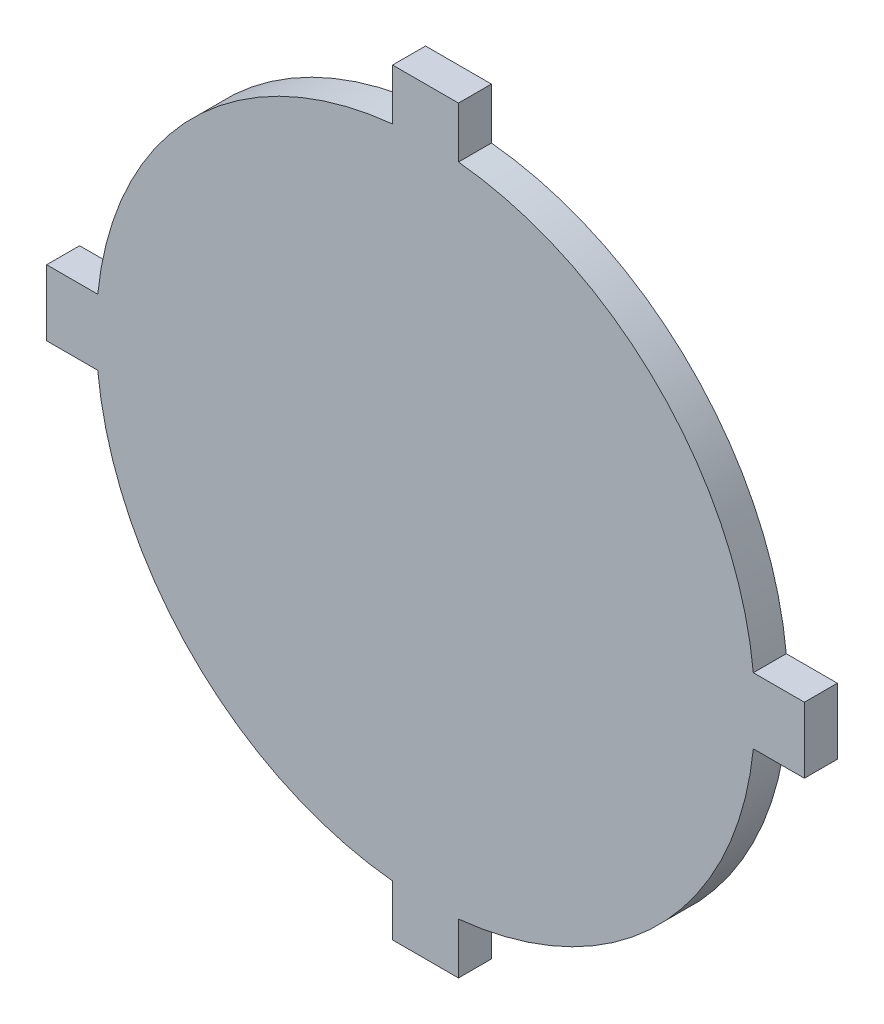
SolidWorks part; units mm, degrees
ref_plane "前视基准面" through (0, 0, 0) normal (0, 0, 1) x (1, 0, 0)
ref_plane "上视基准面" through (0, 0, 0) normal (0, 1, 0) x (1, 0, 0)
ref_plane "右视基准面" through (0, 0, 0) normal (1, 0, 0) x (0, 0, -1)
other "Configuration Table"
sketch "草图1" plane through (0, 0, 0) normal (0, 0, 1) x (1, 0, 0)
  circle A0 centre (0, 0) radius 20
extrude "凸台-拉伸1" add sketch "草图1" along normal blind 2
sketch "草图2" plane through (0, 0, 0) normal (0, 0, 1) x (1, 0, 0)
  line L1 (19, -2) -> (23, -2)
  line L2 (19, -2) -> (19, 2)
  line L3 (19, 2) -> (23, 2)
  line L4 (23, -2) -> (23, 2)
  line L6 (-2, 19) -> (2, 19)
  line L7 (-2, 19) -> (-2, 23)
  line L8 (-2, 23) -> (2, 23)
  line L9 (2, 19) -> (2, 23)
  line L11 (-23, -2) -> (-19, -2)
  line L12 (-23, -2) -> (-23, 2)
  line L13 (-23, 2) -> (-19, 2)
  line L14 (-19, -2) -> (-19, 2)
  line L16 (-2, -23) -> (2, -23)
  line L17 (-2, -23) -> (-2, -19)
  line L18 (-2, -19) -> (2, -19)
  line L19 (2, -23) -> (2, -19)
extrude "凸台-拉伸2" add sketch "草图2" along normal blind 2
